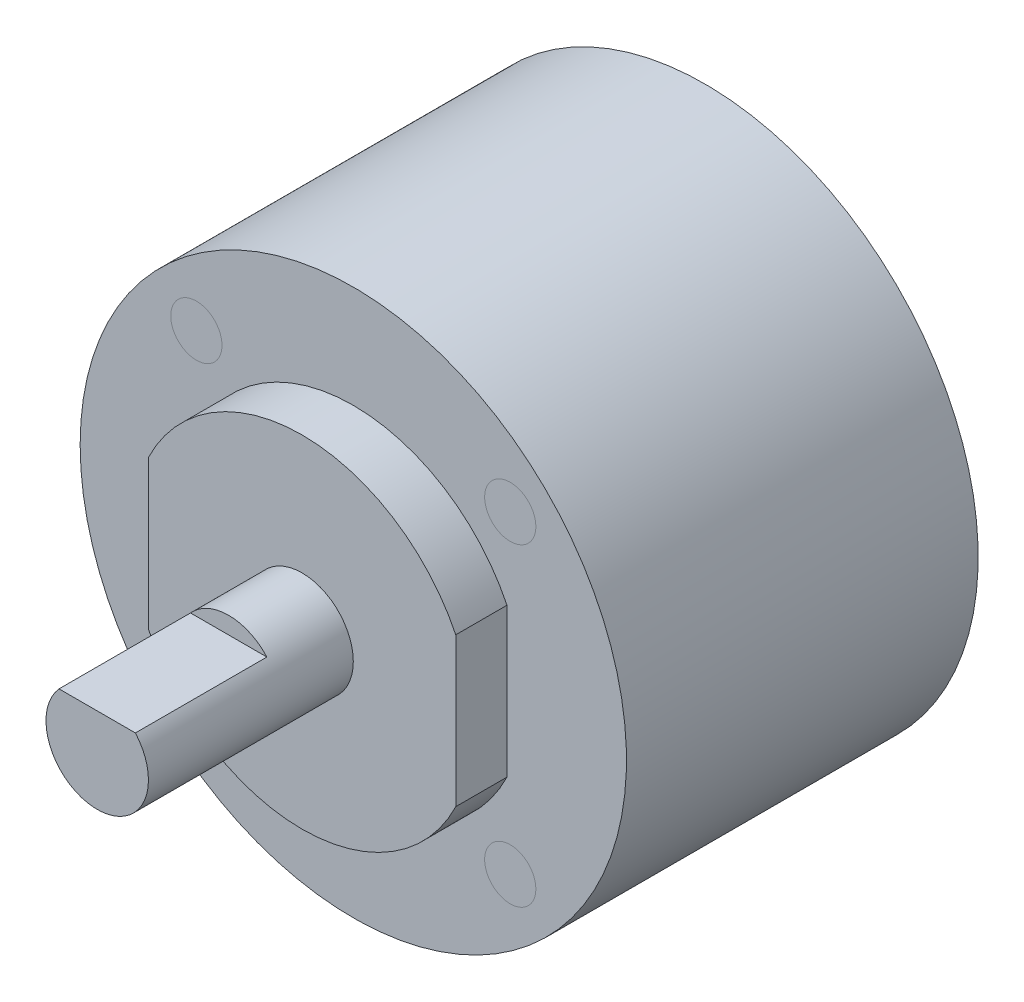
SolidWorks part; units mm, degrees
ref_plane "Front" through (0, 0, 0) normal (0, 0, 1) x (1, 0, 0)
ref_plane "Top" through (0, 0, 0) normal (0, 1, 0) x (1, 0, 0)
ref_plane "Right" through (0, 0, 0) normal (1, 0, 0) x (0, 0, -1)
sketch "ｽｹｯﾁ1" plane through (0, 0, 0) normal (0, 0, 1) x (1, 0, 0)
  circle A0 centre (0, 0) radius 16
  dimension "D1" = 32
extrude "ﾎﾞｽ - 押し出し1" add sketch "ｽｹｯﾁ1" along normal blind 20.6
sketch "ｽｹｯﾁ2" plane through (0, 0, 20.6) normal (0, 0, 1) x (1, 0, 0)
  line L0 (-9, 4.3589) -> (-9, -4.3589)
  line L1 (9, -4.3589) -> (9, 4.3589)
  arc A0 (-9, -4.3589) -> (9, -4.3589) centre (0, 0) ccw
  arc A1 (9, 4.3589) -> (-9, 4.3589) centre (0, 0) ccw
  dimension "D2" = 20
  dimension "D1" = 18
extrude "ﾎﾞｽ - 押し出し2" add sketch "ｽｹｯﾁ2" along normal blind 3
sketch "ｽｹｯﾁ3" plane through (0, 0, 23.6) normal (0, 0, 1) x (1, 0, 0)
  circle A0 centre (0, 0) radius 3
  dimension "D1" = 6
extrude "ﾎﾞｽ - 押し出し3" add sketch "ｽｹｯﾁ3" along normal blind 16.3
sketch "ｽｹｯﾁ4" plane through (0, 0, 39.9) normal (0, 0, 1) x (1, 0, 0)
  line L0 (-2.2361, 2) -> (2.2361, 2)
  arc A0 (-2.2361, 2) -> (2.2361, 2) centre (0, 0) cw
  circle A1 centre (0, 0) radius 3 construction
  dimension "D1" = 2
extrude "ｶｯﾄ - 押し出し1" cut sketch "ｽｹｯﾁ4" against normal blind 12
sketch "ｽｹｯﾁ5" plane through (0, 0, 20.6) normal (0, 0, 1) x (1, 0, 0)
  line L0 (0, 0) -> (9.1924, 9.1924) construction
  line L1 (0, 0) -> (9.1924, -9.1924) construction
  line L2 (0, 0) -> (-9.1924, -9.1924) construction
  line L3 (0, 0) -> (-9.1924, 9.1924) construction
  line L4 (0, 0) -> (16, 0) construction
  circle A0 centre (9.1924, 9.1924) radius 1.5
  circle A1 centre (9.1924, -9.1924) radius 1.5
  circle A2 centre (-9.1924, -9.1924) radius 1.5
  circle A3 centre (-9.1924, 9.1924) radius 1.5
  circle A4 centre (0, 0) radius 16 construction
  point P12 (0, 0)
  dimension "D1" = 3
  dimension "D2" = 13
  dimension "D4" = 45
  dimension "D3" = 4
split line "分割ﾗｲﾝ1"
sketch "ｽｹｯﾁ6" plane through (0, 0, 0) normal (0, 0, -1) x (-1, 0, 0)
  line L0 (-11.3137, -11.3137) -> (11.3137, 11.3137) construction
  line L1 (-16, 0) -> (16, 0) construction
  circle A0 centre (0, 0) radius 16 construction
  circle A1 centre (-5.6569, -5.6569) radius 1.55
  circle A2 centre (5.6569, 5.6569) radius 1.55
  dimension "D2" = 8
  dimension "D3" = 16
  dimension "D4" = 3.1
  dimension "D1" = 45
split line "分割ﾗｲﾝ2"
sketch "ｽｹｯﾁ7" plane through (0, 0, 39.9) normal (0, 0, 1) x (1, 0, 0)
  circle A0 centre (0, 0) radius 3
  arc A1 (-2.2361, 2) -> (2.2361, 2) centre (0, 0) ccw construction
extrude "ｶｯﾄ - 押し出し2" cut sketch "ｽｹｯﾁ7" against normal blind 4.3
